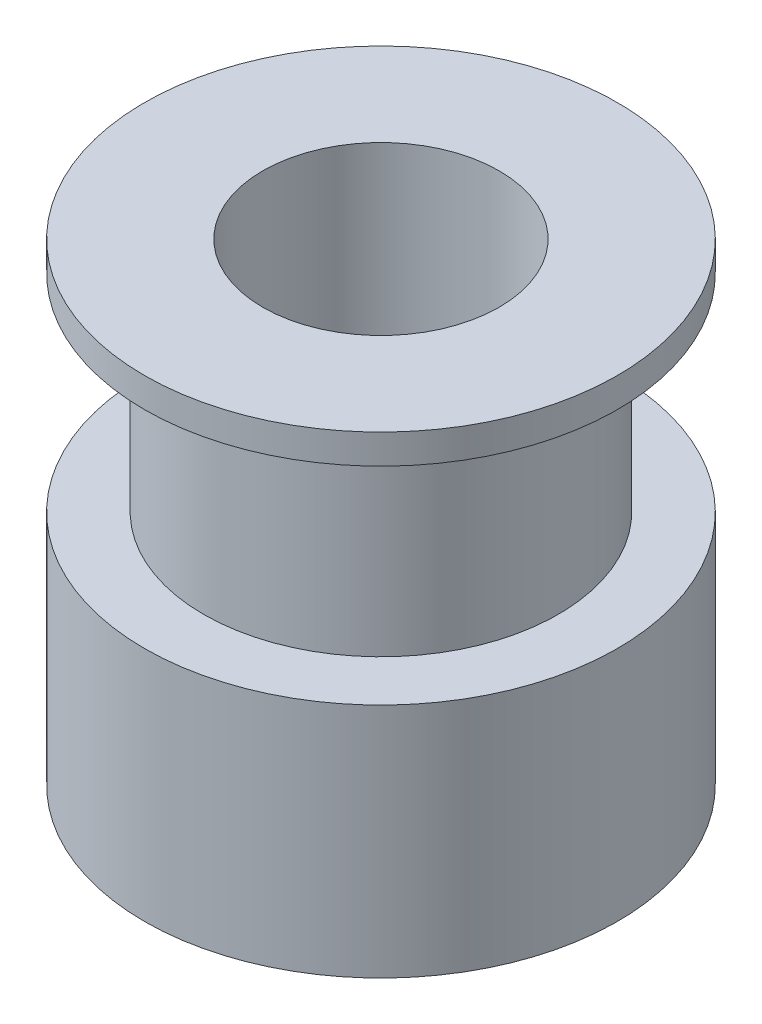
SolidWorks part; units mm, degrees
ref_plane "前视基准面" through (0, 0, 0) normal (0, 0, 1) x (1, 0, 0)
ref_plane "上视基准面" through (0, 0, 0) normal (0, 1, 0) x (1, 0, 0)
ref_plane "右视基准面" through (0, 0, 0) normal (1, 0, 0) x (0, 0, -1)
other "Configuration Table"
sketch "草图1" plane through (0, 0, 0) normal (0, 0, 1) x (1, 0, 0)
  line L0 (0, 15.9) -> (0, -13.55) construction
  line L1 (0, 14.15) -> (-8, 14.15)
  line L2 (-8, 14.15) -> (-8, 13.15)
  line L3 (-8, 13.15) -> (-6, 13.15)
  line L4 (-6, 13.15) -> (-6, 6.15)
  line L5 (-6, 6.15) -> (-8, 6.15)
  line L6 (-8, 6.15) -> (-8, -1.85)
  line L7 (-8, -1.85) -> (0, -1.85)
  line L8 (0, 14.15) -> (0, -1.85)
  dimension "D1" = 1
  dimension "D2" = 8
  dimension "D3" = 6
  dimension "D4" = 16
  dimension "D5" = 7
revolve "旋转1" add sketch "草图1" angle 360 about L0
sketch "草图2" plane through (0, -1.85, 0) normal (0, -1, 0) x (1, 0, 0)
  circle A0 centre (0, 0) radius 4
  dimension "D1" = 8
extrude "切除-拉伸1" cut sketch "草图2" against normal through all
